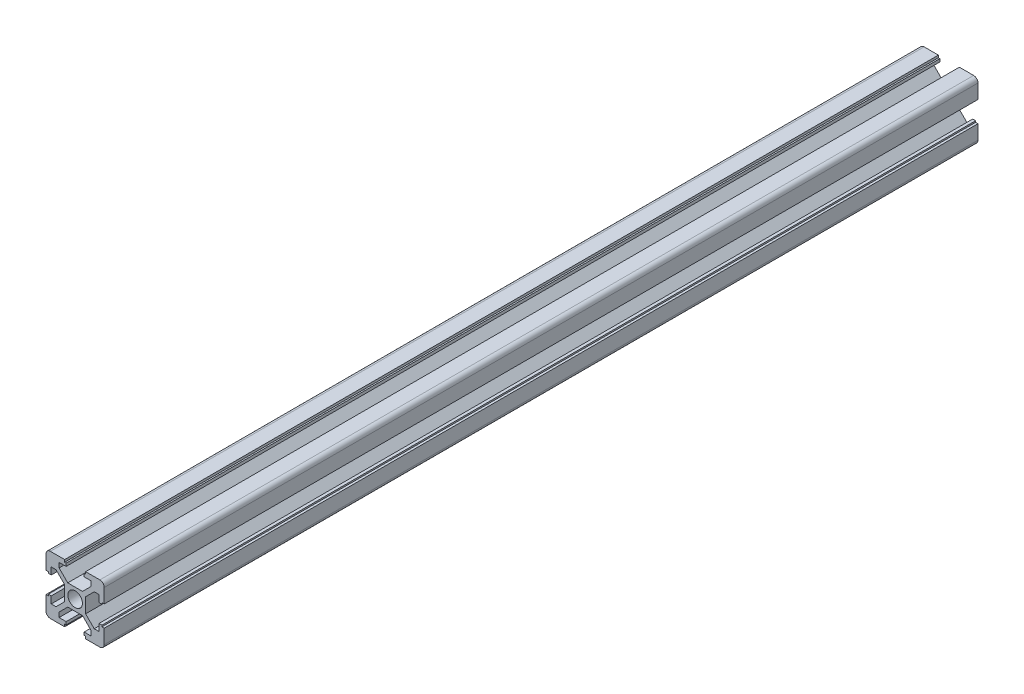
SolidWorks part; units mm, degrees
ref_plane "前视基准面" through (0, 0, 0) normal (0, 0, 1) x (1, 0, 0)
ref_plane "上视基准面" through (0, 0, 0) normal (0, 1, 0) x (1, 0, 0)
ref_plane "右视基准面" through (0, 0, 0) normal (1, 0, 0) x (0, 0, -1)
other "Configuration Table"
sketch "草图1" plane through (0, 0, 0) normal (0, 0, 1) x (1, 0, 0)
  line L0 (-4.4156, 1.3346) -> (-4.4156, 4.4346) construction
  line L1 (-4.4156, 3.874) -> (-4.4156, -1.2047)
  line L2 (1.7237, 4.9346) -> (-3.3549, 4.9346)
  line L3 (2.7844, -1.2047) -> (2.7844, 3.874)
  line L4 (-3.3549, -2.2654) -> (1.7237, -2.2654)
  line L5 (-10.8156, 1.3346) -> (9.1844, 1.3346) construction
  line L6 (-0.8156, 11.3346) -> (-0.8156, -8.6654) construction
  line L7 (-10.8156, 11.3346) -> (-0.8156, 1.3346) construction
  line L8 (-10.8156, 4.9346) -> (-4.4156, 4.9346) construction
  line L9 (-10.0156, 4.4346) -> (-3.9156, 4.4346) construction
  line L10 (-9.0156, 6.8346) -> (-6.3156, 6.8346) construction
  line L11 (-7.3763, 6.8346) -> (-4.4156, 3.874) construction
  line L12 (-10.8156, 9.8346) -> (-10.8156, 4.9346)
  line L13 (-10.8156, 4.9346) -> (-10.0156, 4.9346)
  line L14 (-10.0156, 4.9346) -> (-10.0156, 4.4346)
  line L15 (-10.0156, 4.4346) -> (-9.0156, 4.4346)
  line L16 (-9.0156, 4.4346) -> (-9.0156, 6.8346)
  line L17 (-9.0156, 6.8346) -> (-7.3763, 6.8346)
  line L18 (-7.3763, 6.8346) -> (-4.4156, 3.874)
  line L19 (-3.9156, 10.5346) -> (-3.9156, 9.5346)
  line L20 (-4.4156, 10.5346) -> (-3.9156, 10.5346)
  line L21 (-4.4156, 11.3346) -> (-4.4156, 10.5346)
  line L22 (-9.3156, 11.3346) -> (-4.4156, 11.3346)
  line L23 (-3.9156, 9.5346) -> (-6.3156, 9.5346)
  line L24 (-6.3156, 9.5346) -> (-6.3156, 7.8953)
  line L25 (-6.3156, 7.8953) -> (-3.3549, 4.9346)
  line L26 (9.1844, 11.3346) -> (-0.8156, 1.3346) construction
  line L27 (4.6844, 7.8953) -> (1.7237, 4.9346)
  line L28 (4.6844, 9.5346) -> (4.6844, 7.8953)
  line L29 (2.2844, 9.5346) -> (4.6844, 9.5346)
  line L30 (2.2844, 10.5346) -> (2.2844, 9.5346)
  line L31 (2.7844, 10.5346) -> (2.2844, 10.5346)
  line L32 (2.7844, 11.3346) -> (2.7844, 10.5346)
  line L33 (7.6844, 11.3346) -> (2.7844, 11.3346)
  line L34 (9.1844, 9.8346) -> (9.1844, 4.9346)
  line L35 (9.1844, 4.9346) -> (8.3844, 4.9346)
  line L36 (8.3844, 4.9346) -> (8.3844, 4.4346)
  line L37 (8.3844, 4.4346) -> (7.3844, 4.4346)
  line L38 (7.3844, 4.4346) -> (7.3844, 6.8346)
  line L39 (7.3844, 6.8346) -> (5.7451, 6.8346)
  line L40 (5.7451, 6.8346) -> (2.7844, 3.874)
  line L41 (9.1844, -8.6654) -> (-0.8156, 1.3346) construction
  line L42 (5.7451, -4.1654) -> (2.7844, -1.2047)
  line L43 (7.3844, -4.1654) -> (5.7451, -4.1654)
  line L44 (7.3844, -1.7654) -> (7.3844, -4.1654)
  line L45 (8.3844, -1.7654) -> (7.3844, -1.7654)
  line L46 (8.3844, -2.2654) -> (8.3844, -1.7654)
  line L47 (9.1844, -2.2654) -> (8.3844, -2.2654)
  line L48 (9.1844, -7.1654) -> (9.1844, -2.2654)
  line L49 (7.6844, -8.6654) -> (2.7844, -8.6654)
  line L50 (2.7844, -8.6654) -> (2.7844, -7.8654)
  line L51 (2.7844, -7.8654) -> (2.2844, -7.8654)
  line L52 (2.2844, -7.8654) -> (2.2844, -6.8654)
  line L53 (2.2844, -6.8654) -> (4.6844, -6.8654)
  line L54 (4.6844, -6.8654) -> (4.6844, -5.226)
  line L55 (4.6844, -5.226) -> (1.7237, -2.2654)
  line L56 (-10.8156, -8.6654) -> (-0.8156, 1.3346) construction
  line L57 (-6.3156, -5.226) -> (-3.3549, -2.2654)
  line L58 (-6.3156, -6.8654) -> (-6.3156, -5.226)
  line L59 (-3.9156, -6.8654) -> (-6.3156, -6.8654)
  line L60 (-3.9156, -7.8654) -> (-3.9156, -6.8654)
  line L61 (-4.4156, -7.8654) -> (-3.9156, -7.8654)
  line L62 (-4.4156, -8.6654) -> (-4.4156, -7.8654)
  line L63 (-9.3156, -8.6654) -> (-4.4156, -8.6654)
  line L64 (-10.8156, -7.1654) -> (-10.8156, -2.2654)
  line L65 (-10.8156, -2.2654) -> (-10.0156, -2.2654)
  line L66 (-10.0156, -2.2654) -> (-10.0156, -1.7654)
  line L67 (-10.0156, -1.7654) -> (-9.0156, -1.7654)
  line L68 (-9.0156, -1.7654) -> (-9.0156, -4.1654)
  line L69 (-9.0156, -4.1654) -> (-7.3763, -4.1654)
  line L70 (-7.3763, -4.1654) -> (-4.4156, -1.2047)
  arc A0 (-10.8156, 9.8346) -> (-9.3156, 11.3346) centre (-9.3156, 9.8346) cw
  circle A1 centre (-0.8156, 1.3346) radius 2.5
  arc A2 (7.6844, 11.3346) -> (9.1844, 9.8346) centre (7.6844, 9.8346) cw
  arc A3 (9.1844, -7.1654) -> (7.6844, -8.6654) centre (7.6844, -7.1654) cw
  arc A4 (-9.3156, -8.6654) -> (-10.8156, -7.1654) centre (-9.3156, -7.1654) cw
  point P13 (-0.8156, 1.3346)
  point P84 (-0.8156, 1.3346)
  dimension "D8" = 1.5
  dimension "D9" = 5
  dimension "D1" = 20
  dimension "D2" = 6.2
  dimension "D3" = 7.2
  dimension "D4" = 11
  dimension "D5" = 1.5
  dimension "D6" = 0.8
  dimension "D7" = 1.8
  dimension "D10" = 7.2
extrude "凸台-拉伸1" add sketch "草图1" along normal blind 300 contours A1 | L34 L35 L36 L37 L38 L39 L40 L3 L42 L43 L44 L45 L46 L47 L48 A3 L49 L50 L51 L52 L53 L54 L55 L4 L57 L58 L59 L60 L61 L62 L63 A4 L64 L65 L66 L67 L68 L69 L70 L1 L18 L17 L16 L15 L14 L13 L12 A0 L22 L21 L20 L19 L23 L24 L25 L2 L27 L28 L29 L30 L31 L32 L33 A2
sketch "草图2" plane through (2.7844, 0, 0) normal (1, 0, 0) x (0, 0, -1)
  circle A0 centre (-250, 1.3346) radius 1.75
  circle A1 centre (-50, 1.3346) radius 1.75
extrude "切除-拉伸1" cut sketch "草图2" against normal blind 39
